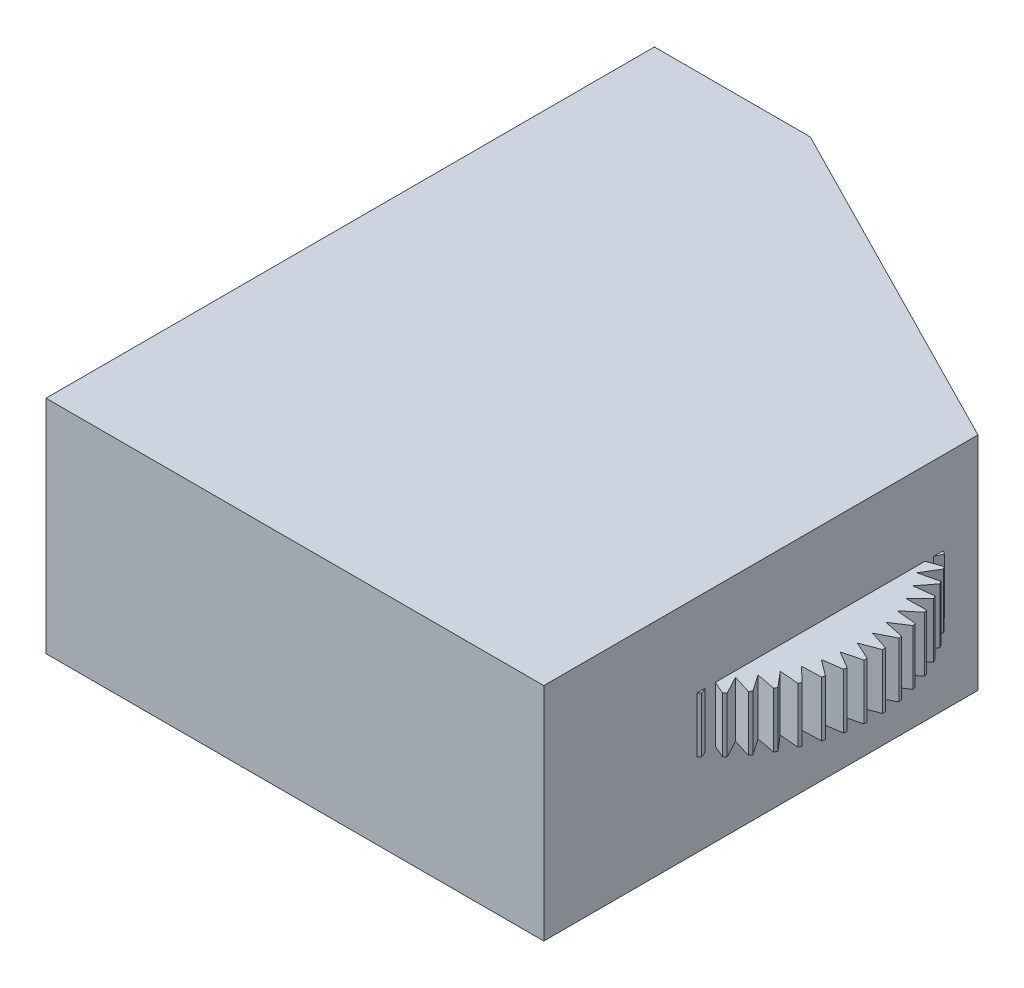
SolidWorks part; units mm, degrees
ref_plane "Front Plane" through (0, 0, 0) normal (0, 0, 1) x (1, 0, 0)
ref_plane "Top Plane" through (0, 0, 0) normal (0, 1, 0) x (1, 0, 0)
ref_plane "Right Plane" through (0, 0, 0) normal (1, 0, 0) x (0, 0, -1)
sketch "Sketch1" plane through (0, 0, 0) normal (0, 1, 0) x (1, 0, 0)
  line L0 (0, 20.6375) -> (0, 34.925)
  line L1 (0, 0) -> (7.9375, 0)
  line L2 (0, 0) -> (0, 15.875)
  line L3 (0, 34.925) -> (28.575, 34.925)
  line L4 (28.575, 0) -> (28.575, 34.925)
  line L13 (12.7, 0) -> (28.575, 0)
  line L14 (0, 15.875) -> (0, 20.6375)
  line L15 (7.9375, 0) -> (12.7, 0)
  dimension "D1" = 28.575
  dimension "D2" = 34.925
extrude "Boss-Extrude3" add sketch "Sketch1" along normal blind 12.7
ref_plane "Plane4" through (0, 4.7625, 0) normal (0, 1, 0) x (1, 0, 0)
sketch "Sketch8" plane through (0, 4.7625, 0) normal (0, 1, 0) x (1, 0, 0)
  line L0 (28.575, 0) -> (28.575, 34.925) construction
  line L1 (0, 0) -> (28.575, 0) construction
  line L2 (31.7383, 15.4034) -> (30.6939, 15.875)
  line L3 (30.6939, 15.875) -> (31.7418, 16.271)
  line L4 (30.6425, 14.9434) -> (31.7276, 15.2217)
  line L5 (31.6287, 14.3598) -> (30.6425, 14.9434)
  line L6 (30.4889, 14.023) -> (31.598, 14.1803)
  line L7 (31.4049, 13.3345) -> (30.4889, 14.023)
  line L8 (30.235, 13.1252) -> (31.3547, 13.1595)
  line L9 (31.0697, 12.34) -> (30.235, 13.1252)
  line L10 (29.8839, 12.2607) -> (31.0006, 12.1716)
  line L11 (30.6272, 11.3885) -> (29.8839, 12.2607)
  line L12 (29.4398, 11.4401) -> (30.5399, 11.2287)
  line L13 (30.0826, 10.4914) -> (29.4398, 11.4401)
  line L14 (28.9081, 10.6733) -> (29.9783, 10.3422)
  line L15 (29.4427, 9.6597) -> (28.9081, 10.6733)
  line L16 (28.2953, 9.9697) -> (29.3226, 9.5228)
  line L17 (28.7152, 8.9034) -> (28.2953, 9.9697)
  line L18 (27.6089, 9.3377) -> (28.5807, 8.7806)
  line L19 (27.9088, 8.2317) -> (27.6089, 9.3377)
  line L20 (26.857, 8.7851) -> (27.7617, 8.1245)
  line L21 (27.0335, 7.6529) -> (26.857, 8.7851)
  line L22 (26.049, 8.3186) -> (26.8755, 7.5624)
  line L23 (26.0998, 7.1738) -> (26.049, 8.3186)
  line L24 (25.1945, 7.9438) -> (25.9328, 7.1013)
  line L25 (25.1191, 6.8003) -> (25.1945, 7.9438)
  line L26 (24.304, 7.6653) -> (24.9451, 6.7467)
  line L27 (24.1033, 6.537) -> (24.304, 7.6653)
  line L28 (23.3882, 7.4864) -> (23.9244, 6.5028)
  line L29 (23.0646, 6.3871) -> (23.3882, 7.4864)
  line L30 (22.4584, 7.4093) -> (22.8831, 6.3728)
  line L31 (22.0158, 6.3523) -> (22.4584, 7.4093)
  line L32 (21.5256, 7.4351) -> (21.8338, 6.358)
  line L33 (20.9695, 6.4331) -> (21.5256, 7.4351)
  line L34 (20.6014, 7.5632) -> (20.7892, 6.4588)
  line L35 (19.9384, 6.6285) -> (20.6014, 7.5632)
  line L36 (19.6969, 7.7923) -> (19.762, 6.6739)
  line L37 (18.9351, 6.9362) -> (19.6969, 7.7923)
  line L38 (18.8231, 8.1194) -> (18.7648, 7.0007)
  line L39 (17.9717, 7.3524) -> (18.8231, 8.1194)
  line L40 (17.9906, 8.5407) -> (17.8096, 7.4352)
  line L41 (17.06, 7.872) -> (17.9906, 8.5407)
  line L42 (17.2094, 9.0511) -> (16.9079, 7.9722)
  line L43 (16.2109, 8.4888) -> (17.2094, 9.0511)
  line L44 (16.4892, 9.6443) -> (16.0708, 8.6051)
  line L45 (15.4349, 9.1952) -> (16.4892, 9.6443)
  line L46 (15.8386, 10.3131) -> (15.3084, 9.3262)
  line L47 (14.7412, 9.9827) -> (15.8386, 10.3131)
  line L48 (15.2655, 11.0494) -> (14.63, 10.1268)
  line L49 (14.1385, 10.8417) -> (15.2655, 11.0494)
  line L50 (14.7769, 11.8443) -> (14.0437, 10.9973)
  line L51 (13.6338, 11.7619) -> (14.7769, 11.8443)
  line L52 (14.3786, 12.6881) -> (13.5568, 11.9269)
  line L53 (13.2335, 12.7319) -> (14.3786, 12.6881)
  line L54 (14.0757, 13.5706) -> (13.1751, 12.9044)
  line L55 (12.9423, 13.7402) -> (14.0757, 13.5706)
  line L56 (13.8716, 14.4811) -> (12.9032, 13.918)
  line L57 (12.7638, 14.7743) -> (13.8716, 14.4811)
  line L58 (13.769, 15.4085) -> (12.7445, 14.9553)
  line L59 (12.7001, 15.8218) -> (13.769, 15.4085)
  line L60 (13.769, 16.3415) -> (12.7009, 16.0039)
  line L61 (12.7521, 16.8699) -> (13.769, 16.3415)
  line L62 (13.8716, 17.2689) -> (12.7729, 17.0508)
  line L63 (12.919, 17.906) -> (13.8716, 17.2689)
  line L64 (14.0757, 18.1794) -> (12.9596, 18.0835)
  line L65 (13.1989, 18.9174) -> (14.0757, 18.1794)
  line L66 (14.3786, 19.0619) -> (13.2588, 19.0894)
  line L67 (13.5884, 19.8918) -> (14.3786, 19.0619)
  line L68 (14.7769, 19.9057) -> (13.6668, 20.0562)
  line L69 (14.0827, 20.8176) -> (14.7769, 19.9057)
  line L70 (15.2655, 20.7006) -> (14.1787, 20.9723)
  line L71 (14.6759, 21.6833) -> (15.2655, 20.7006)
  line L72 (15.8386, 21.4369) -> (14.7883, 21.8265)
  line L73 (15.3606, 22.4785) -> (15.8386, 21.4369)
  line L74 (16.4892, 22.1057) -> (15.4881, 22.6085)
  line L75 (16.1287, 23.1936) -> (16.4892, 22.1057)
  line L76 (17.2094, 22.6989) -> (16.2698, 23.3088)
  line L77 (16.9708, 23.8198) -> (17.2094, 22.6989)
  line L78 (17.9906, 23.2093) -> (17.1237, 23.9188)
  line L79 (17.8767, 24.3496) -> (17.9906, 23.2093)
  line L80 (18.8231, 23.6306) -> (18.0395, 24.4311)
  line L81 (18.8354, 24.7765) -> (18.8231, 23.6306)
  line L82 (19.6969, 23.9577) -> (19.0062, 24.8396)
  line L83 (19.8352, 25.0953) -> (19.6969, 23.9577)
  line L84 (20.6014, 24.1868) -> (20.0119, 25.1393)
  line L85 (20.864, 25.3023) -> (20.6014, 24.1868)
  line L86 (21.5256, 24.3149) -> (21.0445, 25.3266)
  line L87 (21.9093, 25.3948) -> (21.5256, 24.3149)
  line L88 (22.4584, 24.3407) -> (22.0914, 25.3991)
  line L89 (22.9585, 25.3717) -> (22.4584, 24.3407)
  line L90 (23.3882, 24.2636) -> (23.1399, 25.356)
  line L91 (23.9988, 25.2334) -> (23.3882, 24.2636)
  line L92 (24.304, 24.0847) -> (24.1773, 25.1978)
  line L93 (25.0175, 24.9815) -> (24.304, 24.0847)
  line L94 (25.1945, 23.8062) -> (25.1911, 24.9264)
  line L95 (26.0023, 24.619) -> (25.1945, 23.8062)
  line L96 (26.049, 23.4314) -> (26.1688, 24.5452)
  line L97 (26.9413, 24.1504) -> (26.049, 23.4314)
  line L98 (26.857, 22.9649) -> (27.0987, 24.0587)
  line L99 (27.8231, 23.5813) -> (26.857, 22.9649)
  line L100 (27.6089, 22.4123) -> (27.9694, 23.4729)
  line L101 (28.6368, 22.9187) -> (27.6089, 22.4123)
  line L102 (28.2953, 21.7803) -> (28.7703, 22.7949)
  line L103 (29.3728, 22.1706) -> (28.2953, 21.7803)
  line L104 (28.9081, 21.0767) -> (29.4918, 22.0328)
  line L105 (30.022, 21.3461) -> (28.9081, 21.0767)
  line L106 (29.4398, 20.3099) -> (30.1251, 21.196)
  line L107 (30.5765, 20.4551) -> (29.4398, 20.3099)
  line L108 (29.8839, 19.4893) -> (30.6626, 20.2947)
  line L109 (31.0297, 19.5086) -> (29.8839, 19.4893)
  line L110 (30.235, 18.6248) -> (31.0975, 19.3396)
  line L111 (31.376, 18.518) -> (30.235, 18.6248)
  line L112 (30.4889, 17.727) -> (31.4248, 18.3426)
  line L113 (31.6112, 17.4952) -> (30.4889, 17.727)
  line L114 (30.6425, 16.8066) -> (31.6404, 17.3155)
  line L115 (31.7325, 16.4529) -> (30.6425, 16.8066)
  line L116 (24.9451, 6.7467) -> (25.1191, 6.8003)
  line L117 (22.8831, 6.3728) -> (23.0646, 6.3871)
  arc A0 (31.7418, 16.271) -> (31.7325, 16.4529) centre (22.225, 15.875) ccw
  arc A1 (31.6404, 17.3155) -> (31.6112, 17.4952) centre (22.225, 15.875) ccw
  arc A2 (31.4248, 18.3426) -> (31.376, 18.518) centre (22.225, 15.875) ccw
  arc A3 (31.7276, 15.2217) -> (31.7383, 15.4034) centre (22.225, 15.875) ccw
  arc A4 (31.598, 14.1803) -> (31.6287, 14.3598) centre (22.225, 15.875) ccw
  arc A5 (31.3547, 13.1595) -> (31.4049, 13.3345) centre (22.225, 15.875) ccw
  arc A6 (31.0006, 12.1716) -> (31.0697, 12.34) centre (22.225, 15.875) ccw
  arc A7 (30.5399, 11.2287) -> (30.6272, 11.3885) centre (22.225, 15.875) ccw
  arc A8 (29.9783, 10.3422) -> (30.0826, 10.4914) centre (22.225, 15.875) ccw
  arc A9 (29.3226, 9.5228) -> (29.4427, 9.6597) centre (22.225, 15.875) ccw
  arc A10 (28.5807, 8.7806) -> (28.7152, 8.9034) centre (22.225, 15.875) ccw
  arc A11 (27.7617, 8.1245) -> (27.9088, 8.2317) centre (22.225, 15.875) ccw
  arc A12 (26.8755, 7.5624) -> (27.0335, 7.6529) centre (22.225, 15.875) ccw
  arc A13 (25.9328, 7.1013) -> (26.0998, 7.1738) centre (22.225, 15.875) ccw
  arc A14 (23.9244, 6.5028) -> (24.1033, 6.537) centre (22.225, 15.875) ccw
  arc A15 (21.8338, 6.358) -> (22.0158, 6.3523) centre (22.225, 15.875) ccw
  arc A16 (20.7892, 6.4588) -> (20.9695, 6.4331) centre (22.225, 15.875) ccw
  arc A17 (19.762, 6.6739) -> (19.9384, 6.6285) centre (22.225, 15.875) ccw
  arc A18 (18.7648, 7.0007) -> (18.9351, 6.9362) centre (22.225, 15.875) ccw
  arc A19 (17.8096, 7.4352) -> (17.9717, 7.3524) centre (22.225, 15.875) ccw
  arc A20 (16.9079, 7.9722) -> (17.06, 7.872) centre (22.225, 15.875) ccw
  arc A21 (16.0708, 8.6051) -> (16.2109, 8.4888) centre (22.225, 15.875) ccw
  arc A22 (15.3084, 9.3262) -> (15.4349, 9.1952) centre (22.225, 15.875) ccw
  arc A23 (14.63, 10.1268) -> (14.7412, 9.9827) centre (22.225, 15.875) ccw
  arc A24 (14.0437, 10.9973) -> (14.1385, 10.8417) centre (22.225, 15.875) ccw
  arc A25 (13.5568, 11.9269) -> (13.6338, 11.7619) centre (22.225, 15.875) ccw
  arc A26 (13.1751, 12.9044) -> (13.2335, 12.7319) centre (22.225, 15.875) ccw
  arc A27 (12.9032, 13.918) -> (12.9423, 13.7402) centre (22.225, 15.875) ccw
  arc A28 (12.7445, 14.9553) -> (12.7638, 14.7743) centre (22.225, 15.875) ccw
  arc A29 (12.7009, 16.0039) -> (12.7001, 15.8218) centre (22.225, 15.875) ccw
  arc A30 (12.7729, 17.0508) -> (12.7521, 16.8699) centre (22.225, 15.875) ccw
  arc A31 (12.9596, 18.0835) -> (12.919, 17.906) centre (22.225, 15.875) ccw
  arc A32 (13.2588, 19.0894) -> (13.1989, 18.9174) centre (22.225, 15.875) ccw
  arc A33 (13.6668, 20.0562) -> (13.5884, 19.8918) centre (22.225, 15.875) ccw
  arc A34 (14.1787, 20.9723) -> (14.0827, 20.8176) centre (22.225, 15.875) ccw
  arc A35 (14.7883, 21.8265) -> (14.6759, 21.6833) centre (22.225, 15.875) ccw
  arc A36 (15.4881, 22.6085) -> (15.3606, 22.4785) centre (22.225, 15.875) ccw
  arc A37 (16.2698, 23.3088) -> (16.1287, 23.1936) centre (22.225, 15.875) ccw
  arc A38 (17.1237, 23.9188) -> (16.9708, 23.8198) centre (22.225, 15.875) ccw
  arc A39 (18.0395, 24.4311) -> (17.8767, 24.3496) centre (22.225, 15.875) ccw
  arc A40 (19.0062, 24.8396) -> (18.8354, 24.7765) centre (22.225, 15.875) ccw
  arc A41 (20.0119, 25.1393) -> (19.8352, 25.0953) centre (22.225, 15.875) ccw
  arc A42 (21.0445, 25.3266) -> (20.864, 25.3023) centre (22.225, 15.875) ccw
  arc A43 (22.0914, 25.3991) -> (21.9093, 25.3948) centre (22.225, 15.875) ccw
  arc A44 (23.1399, 25.356) -> (22.9585, 25.3717) centre (22.225, 15.875) ccw
  arc A45 (24.1773, 25.1978) -> (23.9988, 25.2334) centre (22.225, 15.875) ccw
  arc A46 (25.1911, 24.9264) -> (25.0175, 24.9815) centre (22.225, 15.875) ccw
  arc A47 (26.1688, 24.5452) -> (26.0023, 24.619) centre (22.225, 15.875) ccw
  arc A48 (27.0987, 24.0587) -> (26.9413, 24.1504) centre (22.225, 15.875) ccw
  arc A49 (27.9694, 23.4729) -> (27.8231, 23.5813) centre (22.225, 15.875) ccw
  arc A50 (28.7703, 22.7949) -> (28.6368, 22.9187) centre (22.225, 15.875) ccw
  arc A51 (29.4918, 22.0328) -> (29.3728, 22.1706) centre (22.225, 15.875) ccw
  arc A52 (30.1251, 21.196) -> (30.022, 21.3461) centre (22.225, 15.875) ccw
  arc A53 (30.6626, 20.2947) -> (30.5765, 20.4551) centre (22.225, 15.875) ccw
  arc A54 (31.0975, 19.3396) -> (31.0297, 19.5086) centre (22.225, 15.875) ccw
  dimension "D1" = 6.35
  dimension "D3" = 19.05
  dimension "D2" = 15.875
  dimension "D4" = 57
extrude "Boss-Extrude5" add sketch "Sketch8" along normal blind 3.175
chamfer "Chamfer1" distance 10 angle 63 1 edges at (28.575, 6.35, -34.925)
